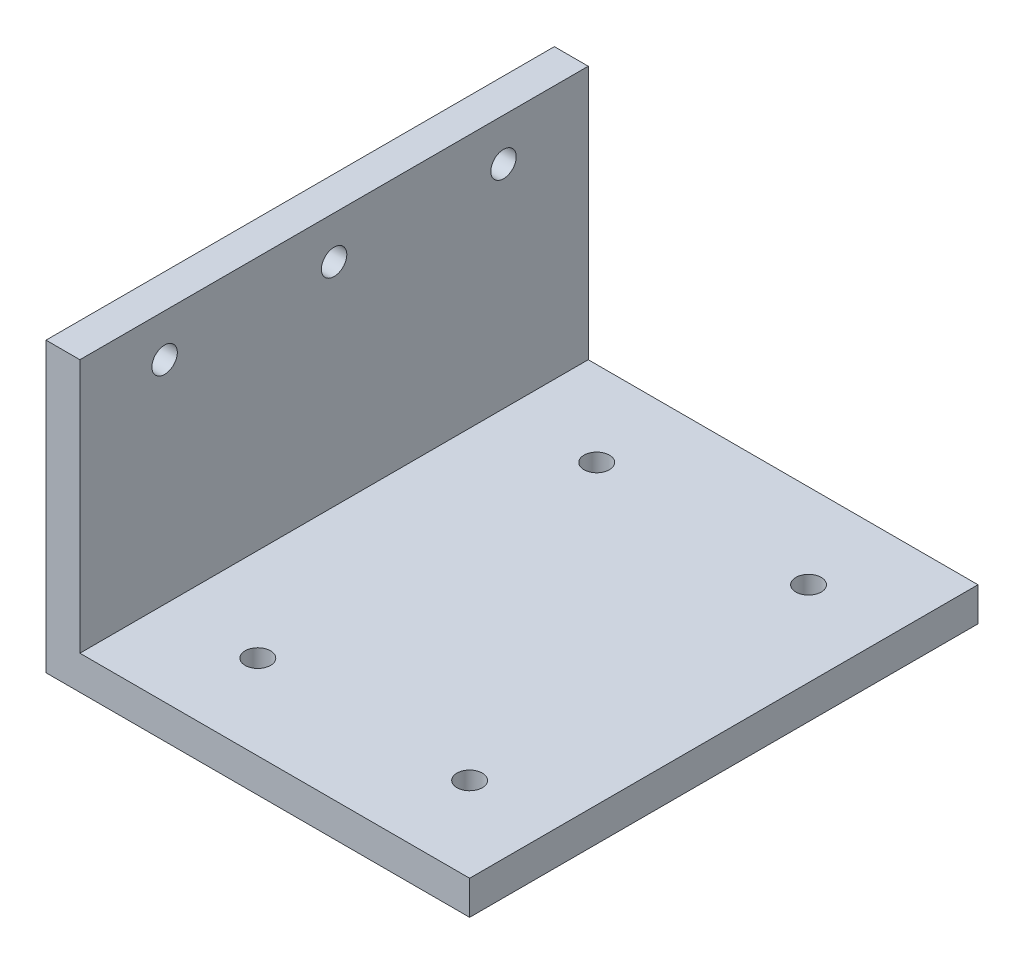
SolidWorks part; units mm, degrees
ref_plane "Plan de face" through (0, 0, 0) normal (0, 0, 1) x (1, 0, 0)
ref_plane "Plan de dessus" through (0, 0, 0) normal (0, 1, 0) x (1, 0, 0)
ref_plane "Plan de droite" through (0, 0, 0) normal (1, 0, 0) x (0, 0, -1)
sketch "Esquisse1" plane through (0, 0, 0) normal (0, 0, 1) x (1, 0, 0)
  line L1 (0, 0) -> (4, 0)
  line L2 (0, 0) -> (0, 50)
  line L3 (0, 50) -> (4, 50)
  line L4 (4, 4) -> (4, 50)
  line L5 (4, 0) -> (50, 0)
  line L7 (4, 4) -> (50, 4)
  line L8 (50, 0) -> (50, 4)
  dimension "D1" = 50
  dimension "D2" = 4
  dimension "D3" = 4
  dimension "D4" = 46
extrude "Extrusion1" add sketch "Esquisse1" along normal blind 60
sketch "Esquisse2" plane through (0, 4, 0) normal (0, 1, 0) x (1, 0, 0)
  line L0 (50, -60) -> (4, -60) construction
  line L1 (50, -60) -> (50, 0) construction
  circle A0 centre (40, -50) radius 1.5
  dimension "D1" = 3
  dimension "D2" = 10
  dimension "D3" = 10
extrude "Extrusion2" cut sketch "Esquisse2" against normal through all
pattern_linear "Répétition linéaire1" count 2 spacing 40 along (0, 0, -1) count 2 spacing 25 along (-1, 0, 0) of "Extrusion2"
sketch "Esquisse3" plane through (0, 0, 0) normal (-1, 0, 0) x (0, 0, 1)
  line L1 (-24.0737, 73.6535) -> (99.6013, 73.6535)
  line L2 (-24.0737, 73.6535) -> (-24.0737, 34)
  line L3 (-24.0737, 34) -> (99.6013, 34)
  line L4 (99.6013, 73.6535) -> (99.6013, 34)
  line L5 (60, 0) -> (0, 0) construction
  dimension "D1" = 34
extrude "Extrusion3" cut sketch "Esquisse3" against normal blind 10
sketch "Esquisse4" plane through (0, 0, 0) normal (-1, 0, 0) x (0, 0, 1)
  line L0 (0, 34) -> (60, 34) construction
  line L1 (60, 34) -> (60, 0) construction
  circle A0 centre (50, 29) radius 1.5
  dimension "D1" = 3
  dimension "D2" = 5
  dimension "D3" = 10
extrude "Extrusion4" cut sketch "Esquisse4" against normal blind 10
pattern_linear "Répétition linéaire2" count 3 spacing 20 along (0, 0, -1) of "Extrusion4"
